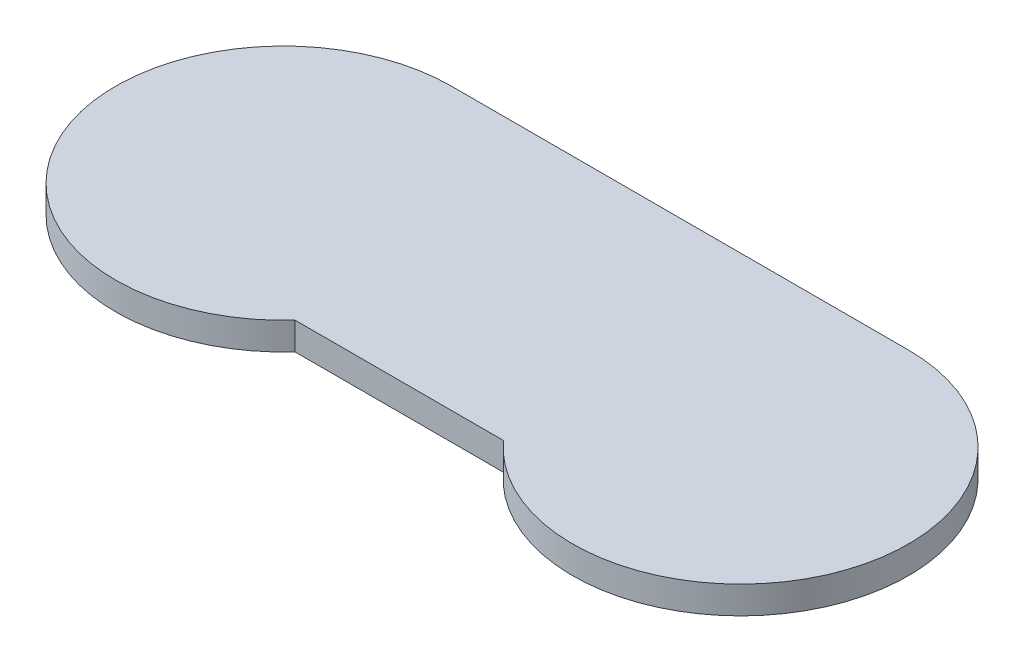
SolidWorks part; units mm, degrees
ref_plane "Front Plane" through (0, 0, 0) normal (0, 0, 1) x (1, 0, 0)
ref_plane "Top Plane" through (0, 0, 0) normal (0, 1, 0) x (1, 0, 0)
ref_plane "Right Plane" through (0, 0, 0) normal (1, 0, 0) x (0, 0, -1)
sketch "Sketch1" plane through (0, 0, 0) normal (0, 1, 0) x (1, 0, 0)
  line L1 (72, -30.5) -> (-72, -30.5) construction
  line L3 (41.5, 30.5) -> (-41.5, 30.5)
  line L5 (72, -30.5) -> (-72, 30.5) construction
  line L6 (72, 30.5) -> (-11.3836, -4.8222) construction
  line L7 (-18.9168, -20.5) -> (18.9168, -20.5)
  line L8 (-58.9884, -24.9881) -> (-72, -30.5) construction
  arc A0 (-41.5, 30.5) -> (-18.9168, -20.5) centre (-41.5, 0) ccw
  arc A1 (18.9168, -20.5) -> (41.5, 30.5) centre (41.5, 0) ccw
  point P0 (0, 0)
  dimension "D4" = 61
  dimension "D2" = 83
  dimension "D1" = 144
  dimension "D3" = 61
  dimension "D6" = 10
extrude "Boss-Extrude1" add sketch "Sketch1" along normal blind 5
